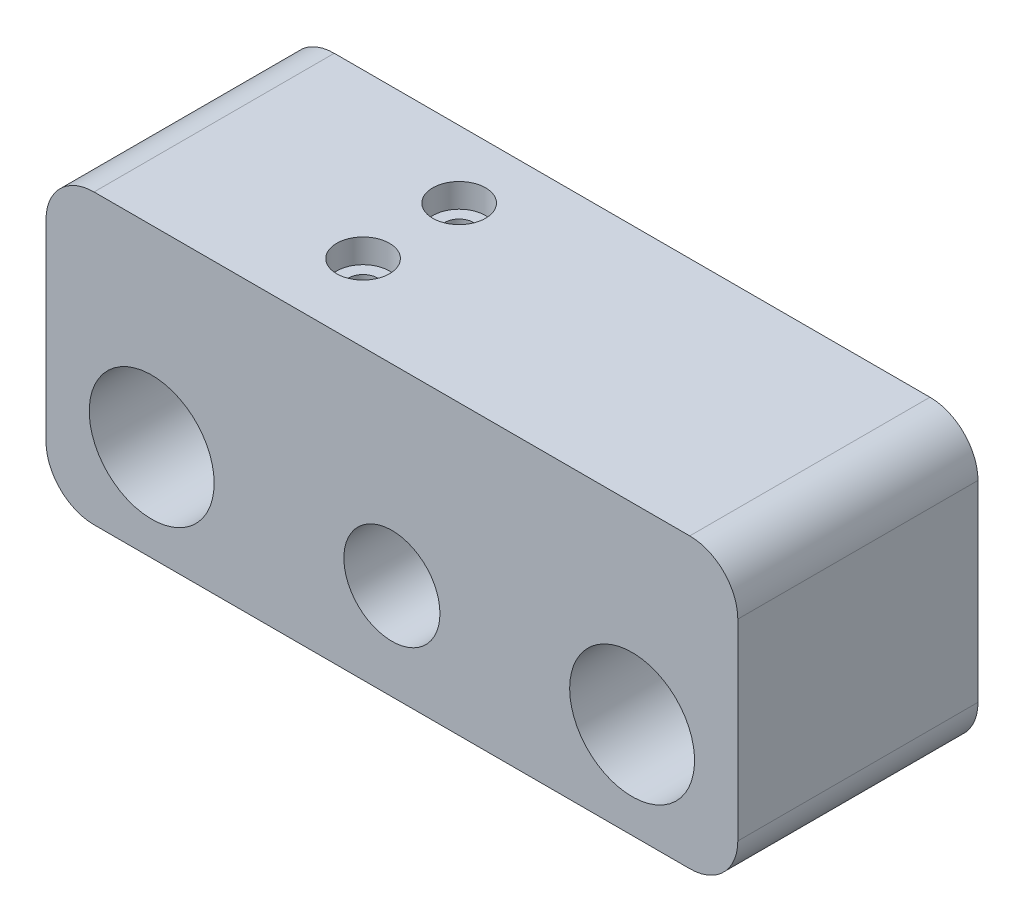
SolidWorks part; units mm, degrees
ref_plane "Front Plane" through (0, 0, 0) normal (0, 0, 1) x (1, 0, 0)
ref_plane "Top Plane" through (0, 0, 0) normal (0, 1, 0) x (1, 0, 0)
ref_plane "Right Plane" through (0, 0, 0) normal (1, 0, 0) x (0, 0, -1)
sketch "Sketch1" plane through (0, 0, 0) normal (0, 0, 1) x (1, 0, 0)
  line L1 (-72, -40) -> (72, -40)
  line L2 (-72, -40) -> (-72, 40)
  line L3 (-72, 40) -> (72, 40)
  line L4 (72, -40) -> (72, 40)
  line L5 (-72, -40) -> (72, 40) construction
  line L6 (-72, 40) -> (72, -40) construction
  point P0 (0, 0)
  dimension "D1" = 80
  dimension "D2" = 144
extrude "Boss-Extrude1" add sketch "Sketch1" along normal blind 50
sketch "Sketch2" plane through (0, 0, 50) normal (0, 0, 1) x (1, 0, 0)
  line L0 (-72, 0) -> (72, 0) construction
  line L1 (-72, 40) -> (-72, -40) construction
  line L2 (72, -40) -> (72, 40) construction
  line L3 (0, 40) -> (0, -40) construction
  line L4 (72, 40) -> (-72, 40) construction
  line L5 (-72, -40) -> (72, -40) construction
  circle A0 centre (0, 0) radius 10
  circle A1 centre (-50, 0) radius 13
  circle A2 centre (50, 0) radius 13
  dimension "D1" = 26
  dimension "D3" = 20
  dimension "D2" = 22
extrude "Cut-Extrude1" cut sketch "Sketch2" against normal up to next
sketch "Sketch3" plane through (0, 0, 50) normal (0, 0, 1) x (1, 0, 0)
  line L5 (72, -40) -> (72, 40) construction
  line L6 (-72, -40) -> (72, -40)
  line L7 (-72, -40) -> (-72, -20)
  line L8 (-72, -20) -> (72, -20)
  line L9 (72, -40) -> (72, -20)
  dimension "D1" = 20
extrude "Cut-Extrude3" cut sketch "Sketch3" against normal up to next
sketch "Sketch5" plane through (0, -20, 0) normal (0, -1, 0) x (1, 0, 0)
  line L0 (-22, 58.6191) -> (-22, -7.1521) construction
  line L1 (-72, 0) -> (-72, 50) construction
  line L3 (72, 50) -> (-72, 50) construction
  circle A0 centre (-22, 34) radius 3
  circle A1 centre (-22, 14) radius 3
  dimension "D4" = 6
  dimension "D1" = 50
  dimension "D2" = 16
  dimension "D3" = 20
extrude "Cut-Extrude4" cut sketch "Sketch5" against normal up to next
fillet "Fillet1" radius 10 1 edges at (72, -20, 25)
fillet "Fillet2" radius 10 1 edges at (72, 40, 25)
fillet "Fillet3" radius 10 1 edges at (-72, 40, 25)
fillet "Fillet4" radius 10 1 edges at (-72, -20, 25)
sketch "Sketch6" plane through (0, 40, 0) normal (0, 1, 0) x (1, 0, 0)
  circle A0 centre (-22, -14) radius 5.5
  circle A1 centre (-22, -34) radius 5.5
  dimension "D1" = 11
  dimension "D2" = 11
extrude "Cut-Extrude5" cut sketch "Sketch6" against normal blind 5
